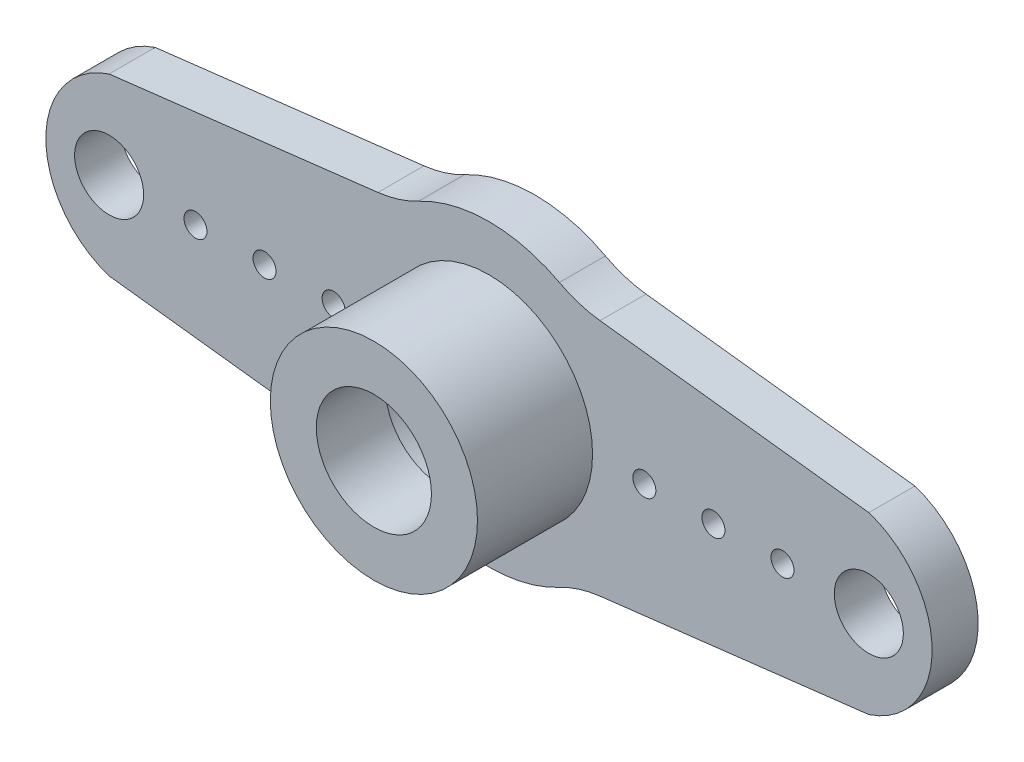
SolidWorks part; units mm, degrees
material "普通碳钢"
ref_plane "前视" through (0, 0, 0) normal (0, 0, 1) x (1, 0, 0)
ref_plane "上视" through (0, 0, 0) normal (0, 1, 0) x (1, 0, 0)
ref_plane "右视" through (0, 0, 0) normal (1, 0, 0) x (0, 0, -1)
sketch "草图1" plane through (0, 0, 0) normal (0, 0, 1) x (1, 0, 0)
  line L1 (0, 0) -> (-33, 0) construction
  line L2 (0, 0) -> (0, -12.3019) construction
  line L3 (16.5, -3.7997) -> (4.8232, -5.1821)
  line L4 (16.5, 3.7997) -> (4.8232, 5.1821)
  line L6 (1.5, 0) -> (33, 0) construction
  line L7 (-16.5, -3.7997) -> (-4.8232, -5.1821)
  line L8 (-16.5, 3.7997) -> (-4.8232, 5.1821)
  arc A0 (-4.8232, 5.1821) -> (-3.0584, 5.7355) centre (-5.411, 10.1475) ccw
  arc A1 (-16.5, 3.7997) -> (-16.5, -3.7997) centre (-15.25, 0) ccw
  arc A2 (16.5, 3.7997) -> (16.5, -3.7997) centre (15.25, 0) cw
  arc A3 (3.0584, 5.7355) -> (-3.0584, 5.7355) centre (0, 0) ccw
  arc A4 (-3.0584, -5.7355) -> (3.0584, -5.7355) centre (0, 0) ccw
  circle A5 centre (-16.5, 0) radius 0.5
  circle A6 centre (-12.75, 0) radius 0.5
  circle A7 centre (-9.75, 0) radius 0.5
  circle A8 centre (-6.75, 0) radius 0.5
  circle A9 centre (-3.75, 0) radius 0.5
  circle A10 centre (3.75, 0) radius 0.5
  circle A11 centre (6.75, 0) radius 0.5
  circle A12 centre (9.75, 0) radius 0.5
  circle A13 centre (12.75, 0) radius 0.5
  circle A14 centre (16.5, 0) radius 0.5
  arc A15 (3.0584, 5.7355) -> (4.8232, 5.1821) centre (5.411, 10.1475) ccw
  arc A16 (3.0584, -5.7355) -> (4.8232, -5.1821) centre (5.411, -10.1475) cw
  arc A17 (-4.8232, -5.1821) -> (-3.0584, -5.7355) centre (-5.411, -10.1475) cw
  point P14 (-3.75, 5.3092)
  point P41 (3.75, 5.3092)
  point P44 (3.75, -5.3092)
  point P47 (-3.75, -5.3092)
  dimension "D1" = 6.5
  dimension "D2" = 8
  dimension "D3" = 38.5
  dimension "D4" = 1
  dimension "D5" = 33
  dimension "D6" = 3
  dimension "D7" = 3
  dimension "D8" = 3
  dimension "D9" = 3.75
  dimension "D10" = 7.5
  dimension "D11" = 5
extrude "凸台-拉伸1" add sketch "草图1" along normal blind 2
sketch "草图2" plane through (0, 0, 2) normal (0, 0, 1) x (1, 0, 0)
  circle A0 centre (0, 0) radius 4.5
  circle A1 centre (0, 0) radius 2.5
  dimension "D1" = 9
  dimension "D2" = 5
extrude "凸台-拉伸2" add sketch "草图2" along normal blind 5
sketch "草图3" plane through (0, 0, 0) normal (0, 0, -1) x (-1, 0, 0)
  circle A0 centre (0, 0) radius 3.5
  dimension "D1" = 7
extrude "切除-拉伸1" cut sketch "草图3" against normal blind 4
sketch "草图4" plane through (0, 0, 0) normal (0, 0, -1) x (-1, 0, 0)
  line L0 (19.25, 0) -> (-19.25, 0)
  arc A0 (16.5, -3.7997) -> (16.5, 3.7997) centre (15.25, 0) ccw construction
  arc A1 (-16.5, 3.7997) -> (-16.5, -3.7997) centre (-15.25, 0) ccw construction
sketch "草图5" plane through (0, 0, 2) normal (0, 0, 1) x (1, 0, 0)
  circle A0 centre (16.5, 0) radius 1.5
  circle A1 centre (-16.5, 0) radius 1.5
  dimension "D1" = 3
  dimension "D2" = 3
extrude "切除-拉伸2" cut sketch "草图5" against normal blind 10
